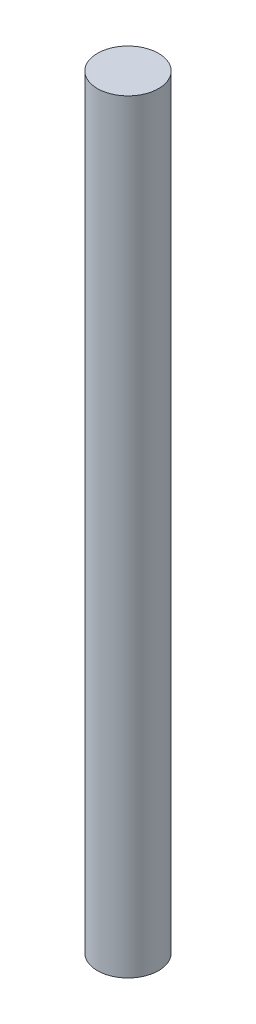
SolidWorks part; units mm, degrees
ref_plane "Front Plane" through (0, 0, 0) normal (0, 0, 1) x (1, 0, 0)
ref_plane "Top Plane" through (0, 0, 0) normal (0, 1, 0) x (1, 0, 0)
ref_plane "Right Plane" through (0, 0, 0) normal (1, 0, 0) x (0, 0, -1)
sketch "Sketch1" plane through (0, 0, 0) normal (0, 1, 0) x (1, 0, 0)
  circle A0 centre (0, 0) radius 8
extrude "Boss-Extrude1" add sketch "Sketch1" along normal blind 200
